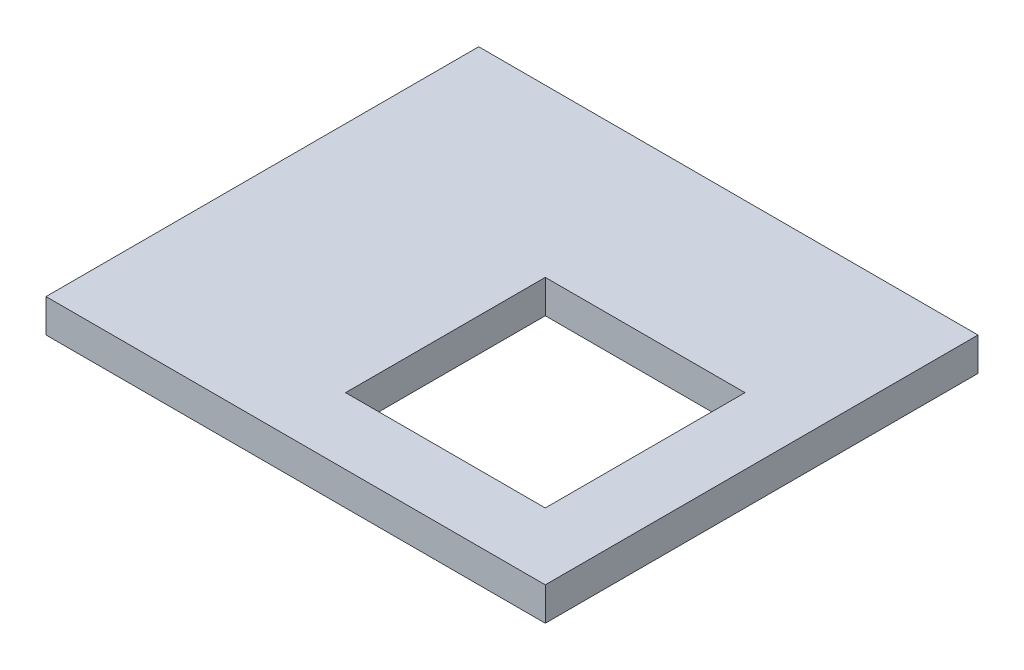
SolidWorks part; units mm, degrees
ref_plane "정면" through (0, 0, 0) normal (0, 0, 1) x (1, 0, 0)
ref_plane "윗면" through (0, 0, 0) normal (0, 1, 0) x (1, 0, 0)
ref_plane "우측면" through (0, 0, 0) normal (1, 0, 0) x (0, 0, -1)
sketch "스케치1" plane through (0, 0, 0) normal (0, 1, 0) x (1, 0, 0)
  line L1 (7.5, -6.5) -> (-7.5, -6.5)
  line L2 (7.5, -6.5) -> (7.5, 6.5)
  line L3 (7.5, 6.5) -> (-7.5, 6.5)
  line L4 (-7.5, -6.5) -> (-7.5, 6.5)
  line L5 (7.5, -6.5) -> (-7.5, 6.5) construction
  line L6 (7.5, 6.5) -> (-7.5, -6.5) construction
  point P0 (0, 0)
  dimension "D1" = 15
  dimension "D2" = 13
extrude "보스-돌출1" add sketch "스케치1" along normal blind 4
sketch "스케치2" plane through (0, 0, 0) normal (0, 1, 0) x (1, 0, 0)
  line L0 (-7.5, -6.5) -> (7.5, -6.5) construction
  line L1 (-6.5, 9.5) -> (6.5, 9.5)
  line L2 (-6.5, 9.5) -> (-6.5, -5.5)
  line L3 (-6.5, -5.5) -> (6.5, -5.5)
  line L4 (6.5, 9.5) -> (6.5, -5.5)
  line L5 (7.5, -6.5) -> (7.5, 6.5) construction
  dimension "D1" = 13
  dimension "D2" = 15
  dimension "D3" = 1
  dimension "D4" = 1
extrude "컷-돌출1" cut sketch "스케치2" along normal blind 4 from offset 1
sketch "스케치3" plane through (0, 0, 0) normal (0, 1, 0) x (1, 0, 0)
  line L1 (7.5, -6.5) -> (-7.5, -6.5)
  line L2 (7.5, -6.5) -> (7.5, 6.5)
  line L3 (7.5, 6.5) -> (-7.5, 6.5)
  line L4 (-7.5, -6.5) -> (-7.5, 6.5)
  line L5 (7.5, -6.5) -> (-7.5, 6.5) construction
  line L6 (7.5, 6.5) -> (-7.5, -6.5) construction
  point P0 (0, 0)
extrude "보스-돌출3" add sketch "스케치3" along normal blind 1 from offset 4 separate body
sketch "스케치4" plane through (0, 0, 0) normal (0, 1, 0) x (1, 0, 0)
  line L0 (-7.5, -6.5) -> (7.5, -6.5) construction
  line L1 (-0.5, 1.5) -> (5.5, 1.5)
  line L2 (-0.5, 1.5) -> (-0.5, -4.5)
  line L3 (-0.5, -4.5) -> (5.5, -4.5)
  line L4 (5.5, 1.5) -> (5.5, -4.5)
  line L5 (7.5, -6.5) -> (7.5, 6.5) construction
  dimension "D1" = 6
  dimension "D2" = 6
  dimension "D3" = 2
  dimension "D4" = 2
extrude "컷-돌출2" cut sketch "스케치4" against normal blind 1 from surface at 5 starting at face at (0, 5, 0)
sketch "스케치6" plane through (0, 0, 0) normal (0, -1, 0) x (1, 0, 0)
  line L4 (-7.5, 6.5) -> (-7.5, -6.5)
  line L5 (-7.5, -6.5) -> (7.5, -6.5)
  line L6 (7.5, -6.5) -> (7.5, 6.5)
  line L7 (7.5, 6.5) -> (-7.5, 6.5)
  line L8 (-7.5, 6.5) -> (-7.5, -6.5)
  line L9 (-7.5, -6.5) -> (7.5, -6.5)
  line L10 (7.5, -6.5) -> (7.5, 6.5)
  line L11 (7.5, 6.5) -> (-7.5, 6.5)
  dimension "D1" = 0
extrude "컷-돌출4" cut sketch "스케치6" against normal blind 4
